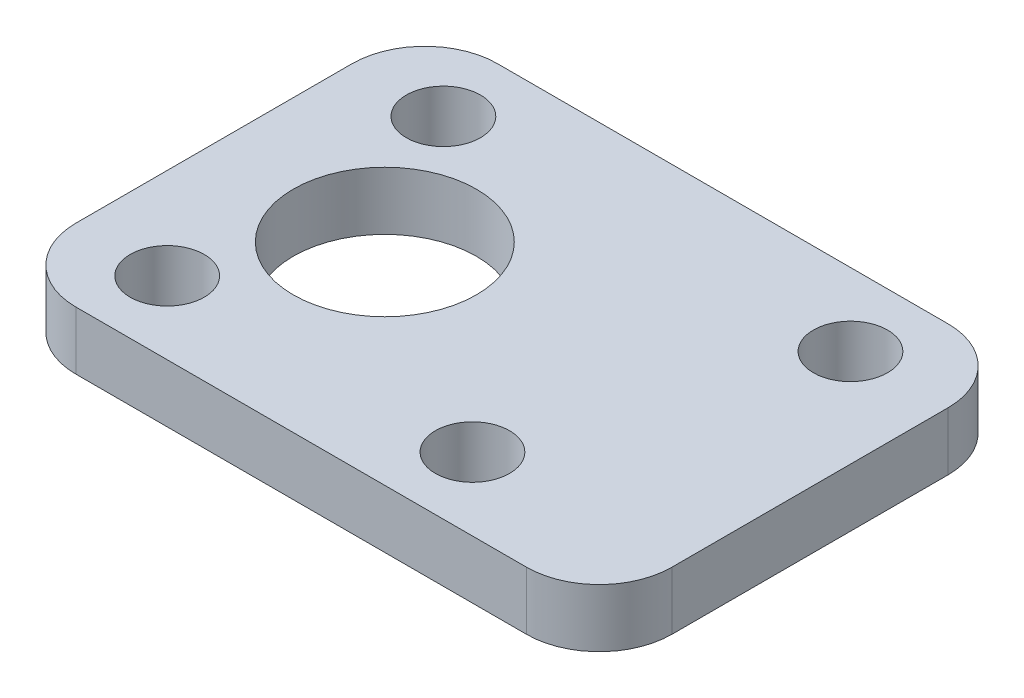
SolidWorks part; units mm, degrees
ref_plane "Front Plane" through (0, 0, 0) normal (0, 0, 1) x (1, 0, 0)
ref_plane "Top Plane" through (0, 0, 0) normal (0, 1, 0) x (1, 0, 0)
ref_plane "Right Plane" through (0, 0, 0) normal (1, 0, 0) x (0, 0, -1)
sketch "Sketch1" plane through (0, 0, 0) normal (0, 1, 0) x (1, 0, 0)
  line L1 (0, 0) -> (82, 0)
  line L2 (0, 0) -> (0, 58)
  line L3 (0, 58) -> (82, 58)
  line L4 (82, 0) -> (82, 58)
  line L5 (0, 58) -> (82, 58) construction
  line L6 (0, 58) -> (0, 118.9)
  line L7 (0, 29) -> (82, 29) construction
  line L8 (0, 118.9) -> (82, 118.9)
  line L9 (0, 48) -> (82, 48) construction
  line L10 (82, 58) -> (82, 118.9)
  line L11 (0, 10) -> (82, 10) construction
  circle A4 centre (12.5611, 48) radius 5.1
  circle A5 centre (12.5611, 10) radius 5.1
  circle A6 centre (54.5611, 10) radius 5.1
  circle A7 centre (68.57, 48) radius 5.1
  circle A8 centre (23.5, 29) radius 12.6
  dimension "D10" = 10.2
  dimension "D12" = 42
  dimension "D13" = 40.5
  dimension "D14" = 25.2
  dimension "D15" = 23.5
  dimension "D16" = 45.07
  dimension "D1" = 58
  dimension "D2" = 82
  dimension "D3" = 60.9
  dimension "D8" = 38
  dimension "D9" = 19
extrude "Boss-Extrude1" add sketch "Sketch1" along normal blind 8 contours L1 L4 L3 L2 A8 A7 A6 A5 A4
fillet "Fillet1" radius 10 4 edges at (82, 4, 0) (0, 4, 0) (0, 4, -58) (82, 4, -58)
